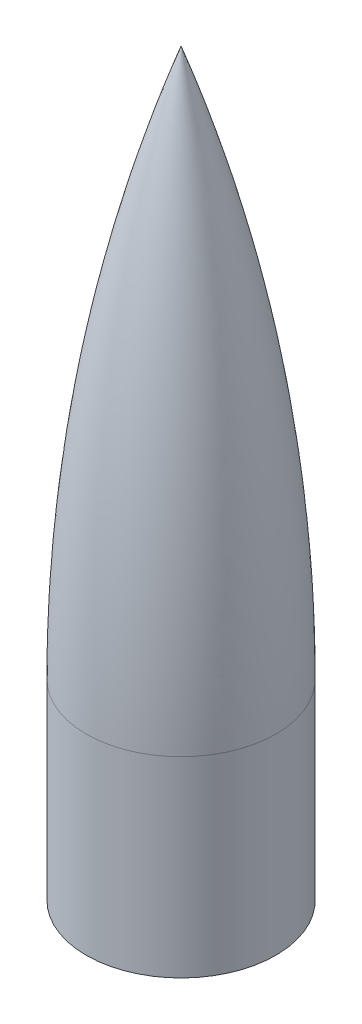
SolidWorks part; units mm, degrees
ref_plane "Front Plane" through (0, 0, 0) normal (0, 0, 1) x (1, 0, 0)
ref_plane "Top Plane" through (0, 0, 0) normal (0, 1, 0) x (1, 0, 0)
ref_plane "Right Plane" through (0, 0, 0) normal (1, 0, 0) x (0, 0, -1)
sketch "Sketch1" plane through (0, 0, 0) normal (0, 0, 1) x (1, 0, 0)
  line L0 (0, 229) -> (0, 0) construction
  line L1 (0, 0) -> (36.6, 0) construction
  line L2 (0, 0) -> (-348.2025, 0) construction
  line L3 (0, 229) -> (0, 219.9054)
  line L6 (36.6, 0) -> (36.6, -80)
  line L7 (36.6, -80) -> (39.6, -80)
  line L8 (39.6, 0) -> (39.6, -80)
  arc A0 (39.6, 0) -> (0, 229) centre (-642.3338, 0) ccw
  arc A1 (36.6, 0) -> (0, 219.9054) centre (-642.3338, 0) ccw
  arc A2 (36.6, 0) -> (-2.8258, 227.9926) centre (-642.3338, 0) ccw construction
  dimension "D1" = 229
  dimension "D2" = 39.6
  dimension "D4" = 80
  dimension "D3" = 3
revolve "Revolve1" add sketch "Sketch1" angle 360 about L0
